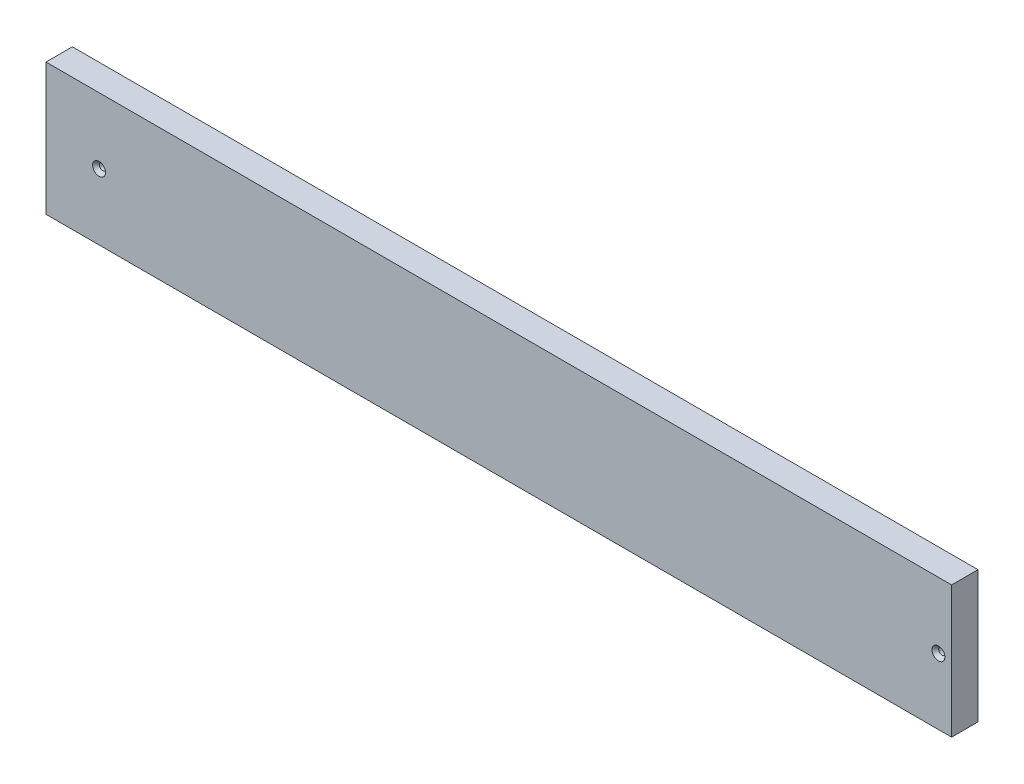
SolidWorks part; units mm, degrees
material "Pine"
ref_plane "Piano frontale" through (0, 0, 0) normal (0, 0, 1) x (1, 0, 0)
ref_plane "Piano superiore" through (0, 0, 0) normal (0, 1, 0) x (1, 0, 0)
ref_plane "Piano destro" through (0, 0, 0) normal (1, 0, 0) x (0, 0, -1)
sketch "Sketch1" plane through (0, 0, 0) normal (0, 0, 1) x (1, 0, 0)
  line L1 (0, 0) -> (51.5, 0)
  line L2 (0, 0) -> (0, 7.5)
  line L3 (0, 7.5) -> (51.5, 7.5)
  line L4 (51.5, 0) -> (51.5, 7.5)
  dimension "D1" = 51.5
  dimension "D2" = 7.5
extrude "Boss-Extrude1" add sketch "Sketch1" along normal blind 1.5
scale "Scale1" scale about origin uniform scaling yes scale factor 10
hole_wizard "CSK for #6 Flat Head Socket Cap Screw4" positions "Sketch9" profile "Sketch10" countersink size "#6" standard "ANSI Inch" end condition through all
sketch "Sketch9" plane through (-500, -171.9185, 15) normal (0, 0, 1) x (0, 1, 0)
  point P0 (209.4185, -1007.5)
sketch "Sketch10" plane through (507.5, 37.5, 15) normal (1, 0, 0) x (0, -1, 0)
  line L0 (0, 0) -> (0, 15)
  line L1 (0, 15) -> (1.905, 15)
  line L2 (1.905, 15) -> (1.905, 2.0454)
  line L3 (1.905, 2.0454) -> (3.683, 0)
  line L4 (3.683, 0) -> (0, 0)
  line L5 (-1.905, 2.0454) -> (-3.683, 0) construction
  line L6 (0, -6.35) -> (0, 107.95) construction
  dimension "Thru Hole Dia." = 3.81
  dimension "Thru Hole Depth" = 15
  dimension "Near C'Sink Dia." = 7.366
  dimension "Near C'Sink Angle" = 82
hole_wizard "CSK for #6 Flat Head Socket Cap Screw5" positions "Sketch11" profile "Sketch12" countersink size "#6" standard "ANSI Inch" end condition through all
sketch "Sketch11" plane through (-500, -171.9185, 15) normal (0, 0, 1) x (0, 1, 0)
  point P0 (209.4185, -530.1945)
sketch "Sketch12" plane through (30.1945, 37.5, 15) normal (1, 0, 0) x (0, -1, 0)
  line L0 (0, 0) -> (0, 15)
  line L1 (0, 15) -> (1.905, 15)
  line L2 (1.905, 15) -> (1.905, 2.0454)
  line L3 (1.905, 2.0454) -> (3.683, 0)
  line L5 (3.683, 0) -> (0, 0)
  line L6 (-1.905, 2.0454) -> (-3.683, 0) construction
  line L11 (0, -6.35) -> (0, 107.95) construction
  dimension "Thru Hole Dia." = 3.81
  dimension "Thru Hole Depth" = 15
  dimension "Near C'Sink Dia." = 7.366
  dimension "Near C'Sink Angle" = 82
